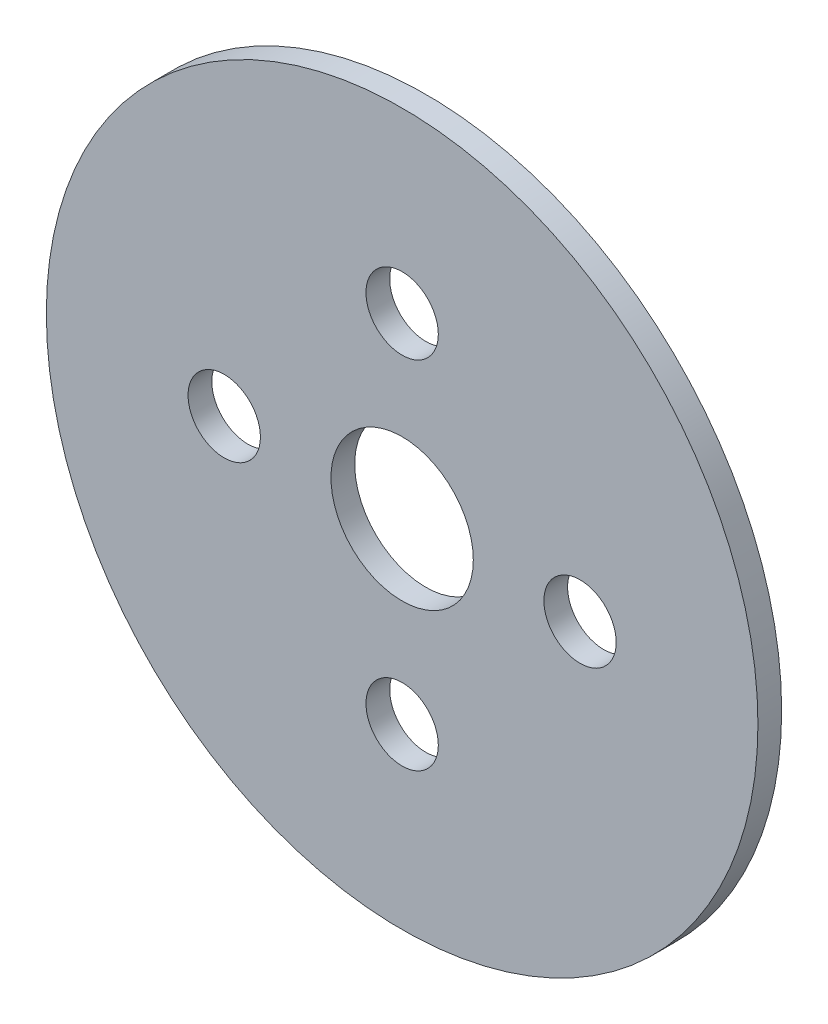
SolidWorks part; units mm, degrees
material "环氧玻璃布层压板"
ref_plane "前视基准面" through (0, 0, 0) normal (0, 0, 1) x (1, 0, 0)
ref_plane "上视基准面" through (0, 0, 0) normal (0, 1, 0) x (1, 0, 0)
ref_plane "右视基准面" through (0, 0, 0) normal (1, 0, 0) x (0, 0, -1)
sketch "草图1" plane through (0, 0, 0) normal (0, 0, 1) x (1, 0, 0)
  circle A0 centre (0, 0) radius 15
  circle A1 centre (0, 0) radius 7.5 construction
  circle A2 centre (0, 7.5) radius 1.525
  circle A3 centre (7.5, 0) radius 1.525
  circle A4 centre (0, -7.5) radius 1.525
  circle A5 centre (-7.5, 0) radius 1.525
  point P5 (-1.044, -16.2694)
  point P7 (0, 0)
  point P15 (0, 0)
  dimension "D1" = 30
  dimension "D2" = 15
  dimension "D3" = 3.05
  dimension "D4" = 4
extrude "凸台-拉伸1" add sketch "草图1" along normal blind 1
sketch "草图2" plane through (0, 0, 1) normal (0, 0, 1) x (1, 0, 0)
  circle A0 centre (0, 7.5) radius 2.525
  circle A1 centre (0, 7.5) radius 1.525 construction
  circle A2 centre (-7.5, 0) radius 2.525
  circle A3 centre (0, -7.5) radius 2.525
  circle A4 centre (7.5, 0) radius 2.525
  circle A5 centre (0, 0) radius 9.5
  dimension "D1" = 1
  dimension "D2" = 19
extrude "切除-拉伸1" [suppressed] cut sketch "草图2" against normal blind 1 contours A4 A5 A0 A2 A3
fillet "圆角1" [suppressed] radius 1.1
sketch "草图3" plane through (0, 0, 1) normal (0, 0, 1) x (1, 0, 0)
  circle A0 centre (0, 0) radius 3
  dimension "D1" = 6
extrude "切除-拉伸2" cut sketch "草图3" against normal blind 1
